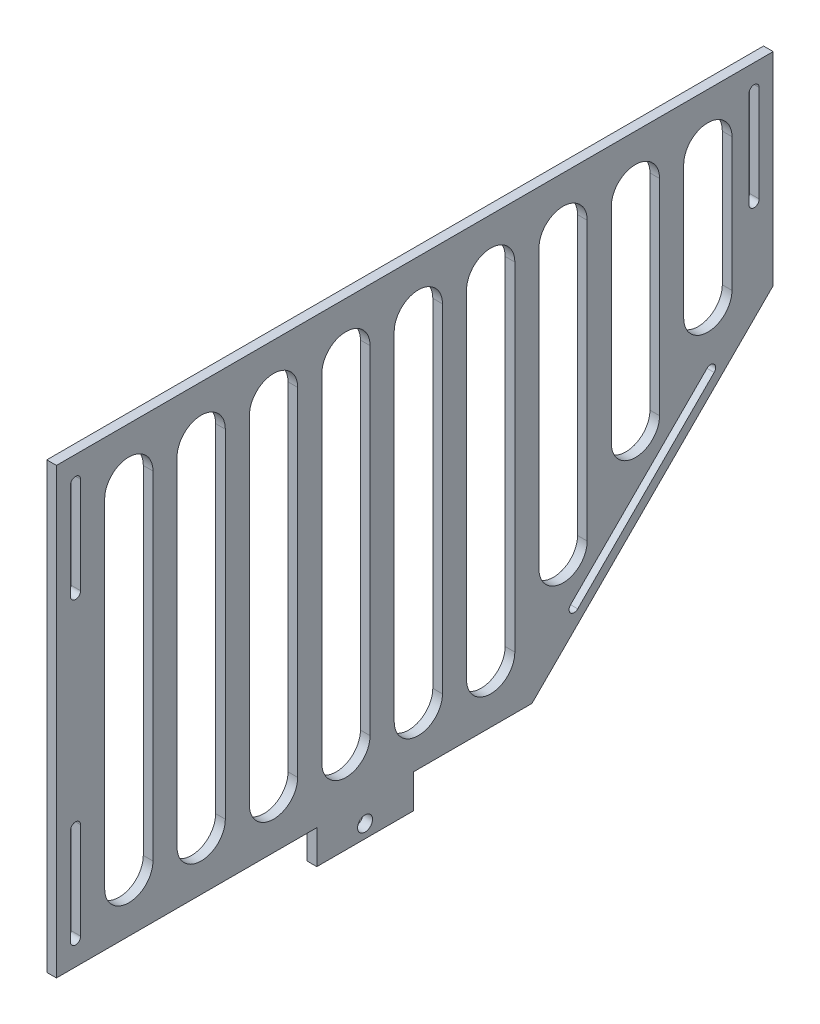
SolidWorks part; units mm, degrees
material "A-玻璃纤维"
ref_plane "前视基准面" through (0, 0, 0) normal (0, 0, 1) x (1, 0, 0)
ref_plane "上视基准面" through (0, 0, 0) normal (0, 1, 0) x (1, 0, 0)
ref_plane "右视基准面" through (0, 0, 0) normal (1, 0, 0) x (0, 0, -1)
sketch "草图2" plane through (0, 0, 0) normal (1, 0, 0) x (0, 0, -1)
  line L1 (-74.275, 46) -> (74.275, 46)
  line L2 (-74.275, 46) -> (-74.275, -46)
  line L3 (-74.275, -46) -> (74.275, -46)
  line L4 (74.275, 46) -> (74.275, -46)
  line L5 (0, -46) -> (0, 46) construction
  line L6 (-74.275, 0) -> (74.275, 0) construction
  point P0 (0, 0)
  dimension "D1" = 148.55
  dimension "D2" = 92
extrude "凸台-拉伸1" add sketch "草图2" along normal blind 2
sketch "草图3" plane through (2, 0, 0) normal (1, 0, 0) x (0, 0, -1)
  line L0 (24.275, -46) -> (74.275, 4)
  line L1 (-74.275, -46) -> (74.275, -46) construction
  line L2 (74.275, -46) -> (74.275, 46) construction
  dimension "D1" = 50
  dimension "D2" = 50
extrude "切除-拉伸1" cut sketch "草图3" against normal blind 2 and the other way through all flip side to cut
sketch "草图4" plane through (2, 0, 0) normal (1, 0, 0) x (0, 0, -1)
  line L0 (-70.315, -41) -> (-70.315, -21) construction
  line L1 (-71.365, -41) -> (-71.365, -21)
  line L2 (-69.265, -41) -> (-69.265, -21)
  line L3 (-74.275, -46) -> (24.275, -46) construction
  line L4 (-74.275, 46) -> (-74.275, -46) construction
  line L5 (-89.4732, 0) -> (86.2417, 0) construction
  line L6 (-70.315, 41) -> (-70.315, 21) construction
  line L7 (-71.365, 41) -> (-71.365, 21)
  line L8 (-69.265, 41) -> (-69.265, 21)
  line L9 (0, 54.2027) -> (0, -13.2498) construction
  line L10 (70.315, 41) -> (70.315, 21) construction
  line L11 (71.365, 41) -> (71.365, 21)
  line L12 (69.265, 41) -> (69.265, 21)
  arc A0 (-71.365, -41) -> (-69.265, -41) centre (-70.315, -41) ccw
  arc A1 (-69.265, -21) -> (-71.365, -21) centre (-70.315, -21) ccw
  arc A2 (-71.365, 41) -> (-69.265, 41) centre (-70.315, 41) cw
  arc A3 (-69.265, 21) -> (-71.365, 21) centre (-70.315, 21) cw
  arc A4 (71.365, 41) -> (69.265, 41) centre (70.315, 41) ccw
  arc A5 (69.265, 21) -> (71.365, 21) centre (70.315, 21) ccw
  point P2 (-70.315, -31)
  point P16 (-70.315, 31)
  point P25 (70.315, 31)
  dimension "D1" = 2.1
  dimension "D2" = 20
  dimension "D3" = 15
  dimension "D4" = 3.96
extrude "切除-拉伸2" cut sketch "草图4" against normal blind 2
sketch "草图5" plane through (2, 0, 0) normal (1, 0, 0) x (0, 0, -1)
  line L0 (-74.275, -46) -> (24.275, -46) construction
  line L1 (-20.315, -46) -> (-0.315, -46)
  line L2 (-20.315, -46) -> (-20.315, -53)
  line L3 (-20.315, -53) -> (-0.315, -53)
  line L4 (-0.315, -46) -> (-0.315, -53)
  line L5 (-74.275, 46) -> (-74.275, -46) construction
  line L6 (-10.315, -53) -> (-10.315, -50.25) construction
  circle A0 centre (-10.315, -50.25) radius 1.55
  dimension "D4" = 3.1
  dimension "D5" = 2.75
  dimension "D1" = 7
  dimension "D2" = 20
  dimension "D3" = 53.96
extrude "凸台-拉伸2" add sketch "草图5" against normal up to surface (2 mm away) up to face at (0, 31, 70.315)
sketch "草图6" plane through (2, 0, 0) normal (1, 0, 0) x (0, 0, -1)
  line L0 (-59.275, -35) -> (-59.275, 35) construction
  line L1 (-64.275, -35) -> (-64.275, 35)
  line L2 (-54.275, -35) -> (-54.275, 35)
  line L3 (15.725, -35) -> (15.725, 35) construction
  line L4 (-44.275, -35) -> (-44.275, 35) construction
  line L5 (-49.275, -35) -> (-49.275, 35)
  line L6 (-39.275, -35) -> (-39.275, 35)
  line L7 (-29.275, -35) -> (-29.275, 35) construction
  line L8 (-34.275, -35) -> (-34.275, 35)
  line L9 (-24.275, -35) -> (-24.275, 35)
  line L10 (-14.275, -35) -> (-14.275, 35) construction
  line L11 (-19.275, -35) -> (-19.275, 35)
  line L12 (-9.275, -35) -> (-9.275, 35)
  line L13 (0.725, -35) -> (0.725, 35) construction
  line L14 (-4.275, -35) -> (-4.275, 35)
  line L15 (5.725, -35) -> (5.725, 35)
  line L16 (-74.275, 46) -> (-74.275, -46) construction
  line L17 (-59.275, 0) -> (0, 0) construction
  line L18 (10.725, -35) -> (10.725, 35)
  line L19 (20.725, -35) -> (20.725, 35)
  line L20 (30.725, -22.5794) -> (30.725, 35) construction
  line L21 (25.725, -22.5794) -> (25.725, 35)
  line L22 (35.725, -22.5794) -> (35.725, 35)
  line L23 (45.725, -7.5794) -> (45.725, 35) construction
  line L24 (40.725, -7.5794) -> (40.725, 35)
  line L25 (50.725, -7.5794) -> (50.725, 35)
  line L26 (19.51, -33.7945) -> (60.8738, 7.5694) construction
  line L27 (24.275, -46) -> (74.275, 4) construction
  line L28 (60.725, 7.4206) -> (60.725, 35) construction
  line L29 (55.725, 7.4206) -> (55.725, 35)
  line L30 (65.725, 7.4206) -> (65.725, 35)
  arc A0 (-64.275, -35) -> (-54.275, -35) centre (-59.275, -35) ccw
  arc A1 (-54.275, 35) -> (-64.275, 35) centre (-59.275, 35) ccw
  arc A2 (-49.275, -35) -> (-39.275, -35) centre (-44.275, -35) ccw
  arc A3 (-39.275, 35) -> (-49.275, 35) centre (-44.275, 35) ccw
  arc A4 (-34.275, -35) -> (-24.275, -35) centre (-29.275, -35) ccw
  arc A5 (-24.275, 35) -> (-34.275, 35) centre (-29.275, 35) ccw
  arc A6 (-19.275, -35) -> (-9.275, -35) centre (-14.275, -35) ccw
  arc A7 (-9.275, 35) -> (-19.275, 35) centre (-14.275, 35) ccw
  arc A8 (-4.275, -35) -> (5.725, -35) centre (0.725, -35) ccw
  arc A9 (5.725, 35) -> (-4.275, 35) centre (0.725, 35) ccw
  arc A10 (10.725, -35) -> (20.725, -35) centre (15.725, -35) ccw
  arc A11 (20.725, 35) -> (10.725, 35) centre (15.725, 35) ccw
  arc A12 (25.725, -22.5794) -> (35.725, -22.5794) centre (30.725, -22.5794) ccw
  arc A13 (35.725, 35) -> (25.725, 35) centre (30.725, 35) ccw
  arc A14 (40.725, -7.5794) -> (50.725, -7.5794) centre (45.725, -7.5794) ccw
  arc A15 (50.725, 35) -> (40.725, 35) centre (45.725, 35) ccw
  arc A16 (55.725, 7.4206) -> (65.725, 7.4206) centre (60.725, 7.4206) ccw
  arc A17 (65.725, 35) -> (55.725, 35) centre (60.725, 35) ccw
  point P2 (-59.275, 0)
  point P10 (-44.275, 0)
  point P17 (-29.275, 0)
  point P24 (-14.275, 0)
  point P31 (0.725, 0)
  point P42 (15.725, 0)
  point P49 (30.725, 6.2103)
  point P56 (45.725, 13.7103)
  point P65 (60.725, 21.2103)
  dimension "D1" = 5
  dimension "D6" = 5
  dimension "D10" = 5
  dimension "D11" = 5
  dimension "D2" = 6
  dimension "D3" = 15
  dimension "D4" = 15
  dimension "D5" = 70
  dimension "D7" = 15
  dimension "D8" = 12
  dimension "D9" = 15
  dimension "D12" = 15
extrude "切除-拉伸3" cut sketch "草图6" against normal blind 2
sketch "草图7" plane through (2, 0, 0) normal (1, 0, 0) x (0, 0, -1)
  line L0 (-74.275, 46) -> (-74.275, -46) construction
  line L1 (-62.275, 20.5) -> (-13.275, 20.5) construction
  line L2 (-62.275, 20.5) -> (-62.275, 10.5) construction
  line L3 (-62.275, 10.5) -> (-13.275, 10.5) construction
  line L4 (-13.275, 20.5) -> (-13.275, 10.5) construction
  line L5 (-37.775, 10.5) -> (-37.775, 20.5) construction
  line L6 (-62.275, 15.5) -> (-13.275, 15.5) construction
  line L7 (74.275, 46) -> (-74.275, 46) construction
  circle A0 centre (-62.275, 10.5) radius 1.55
  circle A1 centre (-13.275, 10.5) radius 1.55
  circle A2 centre (-13.275, 20.5) radius 1.55
  circle A3 centre (-62.275, 20.5) radius 1.55
  point P0 (-37.775, 15.5)
  dimension "D3" = 3.1
  dimension "D5" = 35.5
  dimension "D1" = 10
  dimension "D2" = 49
  dimension "D4" = 12
sketch "草图8" plane through (2, 0, 0) normal (1, 0, 0) x (0, 0, -1)
  line L0 (-64.275, 35) -> (-64.275, -35) construction
  line L1 (-64.275, 7) -> (-54.275, 7)
  line L2 (-64.275, 7) -> (-64.275, 24)
  line L3 (-64.275, 24) -> (-54.275, 24)
  line L4 (-54.275, 7) -> (-54.275, 24)
  line L5 (-54.275, -35) -> (-54.275, 35) construction
  line L6 (-19.275, 35) -> (-19.275, -35) construction
  line L7 (-19.275, 7) -> (-9.275, 7)
  line L8 (-19.275, 7) -> (-19.275, 24)
  line L9 (-19.275, 24) -> (-9.275, 24)
  line L10 (-9.275, 7) -> (-9.275, 24)
  line L11 (-9.275, -35) -> (-9.275, 35) construction
  line L13 (74.275, 46) -> (-74.275, 46) construction
  dimension "D1" = 17
  dimension "D2" = 22
extrude "凸台-拉伸3" [suppressed] add sketch "草图8" against normal up to surface (2 mm away)
extrude "切除-拉伸4" [suppressed] cut sketch "草图7" against normal blind 2
sketch "草图9" plane through (2, 0, 0) normal (1, 0, 0) x (0, 0, -1)
  line L0 (33.0115, -33.0208) -> (61.2958, -4.7365) construction
  line L1 (24.275, -46) -> (74.275, 4) construction
  line L2 (32.2691, -32.2784) -> (60.5534, -3.9941)
  line L3 (33.754, -33.7633) -> (62.0383, -5.479)
  line L4 (49.275, -21) -> (47.1537, -18.8787) construction
  arc A0 (32.2691, -32.2784) -> (33.754, -33.7633) centre (33.0115, -33.0208) ccw
  arc A1 (62.0383, -5.479) -> (60.5534, -3.9941) centre (61.2958, -4.7365) ccw
  point P4 (47.1537, -18.8787)
  point P10 (49.275, -21)
  dimension "D1" = 40
  dimension "D2" = 2.1
  dimension "D3" = 3
extrude "切除-拉伸5" cut sketch "草图9" against normal blind 2
